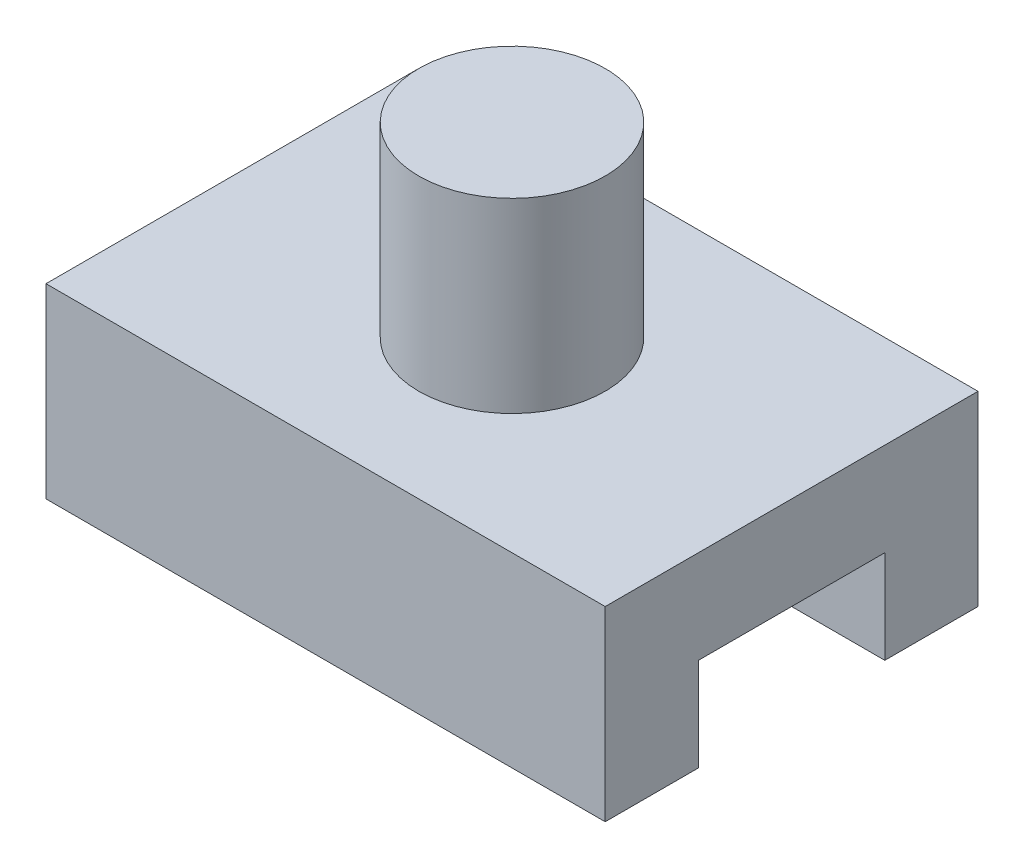
SolidWorks part; units mm, degrees
ref_plane "Front Plane" through (0, 0, 0) normal (0, 0, 1) x (1, 0, 0)
ref_plane "Top Plane" through (0, 0, 0) normal (0, 1, 0) x (1, 0, 0)
ref_plane "Right Plane" through (0, 0, 0) normal (1, 0, 0) x (0, 0, -1)
sketch "Sketch1" plane through (0, 0, 0) normal (0, 1, 0) x (1, 0, 0)
  line L1 (-30, 20) -> (30, 20)
  line L2 (-30, 20) -> (-30, -20)
  line L3 (-30, -20) -> (30, -20)
  line L4 (30, 20) -> (30, -20)
  line L5 (-30, 20) -> (30, -20) construction
  line L6 (-30, -20) -> (30, 20) construction
  point P0 (0, 0)
  dimension "D1" = 60
  dimension "D2" = 40
extrude "Boss-Extrude1" add sketch "Sketch1" along normal blind 20
sketch "Sketch2" plane through (0, 20, 0) normal (0, 1, 0) x (1, 0, 0)
  circle A0 centre (0, 0) radius 10
  dimension "D1" = 20
extrude "Boss-Extrude2" add sketch "Sketch2" along normal blind 20
sketch "Sketch4" plane through (-30, 0, 0) normal (-1, 0, 0) x (0, 0, 1)
  line L0 (-20, 0) -> (20, 0) construction
  line L1 (-10, 0) -> (10, 0)
  line L2 (-10, 0) -> (-10, 10)
  line L3 (-10, 10) -> (10, 10)
  line L4 (10, 0) -> (10, 10)
  line L5 (20, 20) -> (20, 0) construction
  dimension "D1" = 10
  dimension "D2" = 20
  dimension "D3" = 10
extrude "Cut-Extrude1" cut sketch "Sketch4" against normal through all
